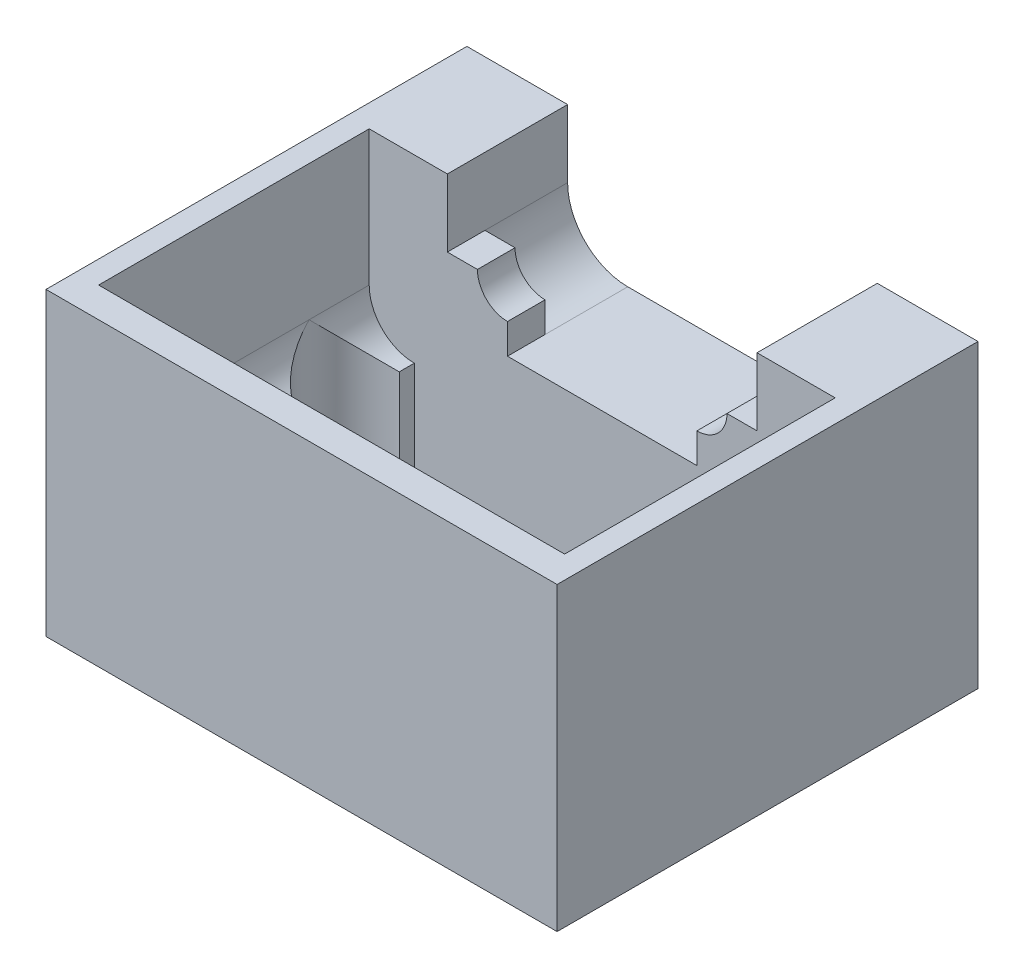
SolidWorks part; units mm, degrees
ref_plane "Front Plane" through (0, 0, 0) normal (0, 0, 1) x (1, 0, 0)
ref_plane "Top Plane" through (0, 0, 0) normal (0, 1, 0) x (1, 0, 0)
ref_plane "Right Plane" through (0, 0, 0) normal (1, 0, 0) x (0, 0, -1)
sketch "Sketch2" plane through (0, 0, 0) normal (0, 1, 0) x (1, 0, 0)
  line L1 (-17, -14) -> (17, -14)
  line L2 (-17, -14) -> (-17, 14)
  line L3 (-17, 14) -> (17, 14)
  line L4 (17, -14) -> (17, 14)
  line L5 (-17, -14) -> (17, 14) construction
  line L6 (-17, 14) -> (17, -14) construction
  point P0 (0, 0)
  dimension "D1" = 34
  dimension "D2" = 28
extrude "Boss-Extrude1" add sketch "Sketch2" along normal blind 20 contours L2 L3 L4 L1
sketch "Sketch3" plane through (0, 20, 0) normal (0, 1, 0) x (1, 0, 0)
  line L0 (-12.5, 6) -> (-12.5, 5)
  line L1 (-12.5, -12) -> (12.5, -12)
  line L3 (-12.5, 6) -> (12.5, 6)
  line L5 (0, 6) -> (0, -12) construction
  line L6 (12.5, -12) -> (12.5, -1)
  line L7 (-12.5, -12) -> (-12.5, -1)
  line L8 (12.5, 6) -> (12.5, 5)
  line L9 (12.5, 5) -> (12.5, -1) construction
  line L10 (-12.5, 5) -> (-12.5, -1) construction
  line L11 (-12.5, 2) -> (12.5, 2) construction
  line L12 (-17, -14) -> (17, -14) construction
  arc A0 (-12.5, 5) -> (-12.5, -1) centre (-12.5, 2) ccw
  arc A1 (12.5, 5) -> (12.5, -1) centre (12.5, 2) cw
  point P9 (-10.1621, 0)
  point P12 (-12.5, 2.5931)
  point P16 (0, 2)
  point P17 (12.5, -12)
  point P18 (0, -4.641)
  point P19 (0, -6.8965)
  dimension "D1" = 3
  dimension "D2" = 25
  dimension "D3" = 18
  dimension "D4" = 4
  dimension "D5" = 2
extrude "Cut-Extrude1" cut sketch "Sketch3" against normal blind 18 contours A0 L7 L1 L6 A1 L8 L3 L0
sketch "Sketch4" plane through (0, 20, 0) normal (0, 1, 0) x (1, 0, 0)
  line L0 (-15.5, 6) -> (-15.5, -12)
  line L1 (-15.5, -12) -> (15.5, -12)
  line L2 (15.5, -12) -> (15.5, 6)
  line L3 (15.5, 6) -> (-15.5, 6)
  line L4 (-12.5, -12) -> (12.5, -12) construction
  line L5 (-12.5, 6) -> (12.5, 6) construction
  arc A2 (-12.5, 5) -> (-12.5, -1) centre (-12.5, 2) ccw construction
  arc A3 (12.5, -1) -> (12.5, 5) centre (12.5, 2) ccw construction
extrude "Cut-Extrude2" cut sketch "Sketch4" against normal blind 9
sketch "Sketch5" plane through (0, 0, 12) normal (0, 0, -1) x (-1, 0, 0)
  circle A0 centre (12.5, 11) radius 3
  circle A1 centre (-12.5, 11) radius 3
  dimension "D1" = 6
extrude "Cut-Extrude3" cut sketch "Sketch5" along normal up to surface (18 mm away) up to face at (0, 11, -6)
sketch "Sketch8" plane through (0, 20, 0) normal (0, 1, 0) x (1, 0, 0)
  line L0 (-12.5, 6) -> (12.5, 6) construction
  line L1 (-6.3, 6) -> (6.3, 6)
  line L2 (-6.3, 6) -> (-6.3, 14)
  line L3 (-6.3, 14) -> (6.3, 14)
  line L4 (6.3, 6) -> (6.3, 14)
  line L5 (0, 14) -> (0, 6) construction
  line L6 (-6.3, 10) -> (6.3, 10) construction
  line L7 (-17, 14) -> (17, 14) construction
  line L8 (0, 6) -> (0, 0) construction
  point P404 (0, 10)
  dimension "D1" = 12.6
extrude "Cut-Extrude5" cut sketch "Sketch8" against normal blind 8.5
sketch "Sketch10" plane through (-6.3, 0, 0) normal (1, 0, 0) x (0, 0, -1)
  line L0 (6, 20) -> (6, 15.5) construction
  line L1 (6, 11.5) -> (6, 20) construction
  line L2 (6, 15.5) -> (14, 15.5)
  line L3 (14, 15.5) -> (14, 19.5)
  line L4 (14, 19.5) -> (8.5, 19.5)
  line L5 (8.5, 19.5) -> (8.5, 17.5)
  line L6 (8.5, 17.5) -> (6, 17.5)
  line L7 (6, 17.5) -> (6, 15.5)
  line L9 (14, 11.5) -> (14, 20) construction
  dimension "D1" = 4.5
  dimension "D2" = 4
  dimension "D3" = 2
  dimension "D5" = 2.5
revolve "Cut-Revolve1" cut sketch "Sketch10" angle 360 about L2
mirror "Mirror1" about plane through (0, 0, 0) normal (1, 0, 0) of "Cut-Revolve1"
sketch "Sketch11" plane through (0, 20, 0) normal (0, 1, 0) x (1, 0, 0)
  line L0 (-15.5, 6) -> (-6.3, 6) construction
  line L1 (-10.3, 6) -> (10.3, 6)
  line L2 (-10.3, 6) -> (-10.3, 14)
  line L3 (-10.3, 14) -> (10.3, 14)
  line L4 (10.3, 6) -> (10.3, 14)
  line L5 (0, 14) -> (0, 6) construction
  line L6 (-10.3, 10) -> (10.3, 10) construction
  line L7 (6.3, 14) -> (17, 14) construction
  point P392 (0, 10)
  dimension "D1" = 20.6
extrude "Cut-Extrude6" cut sketch "Sketch11" against normal blind 4.5
